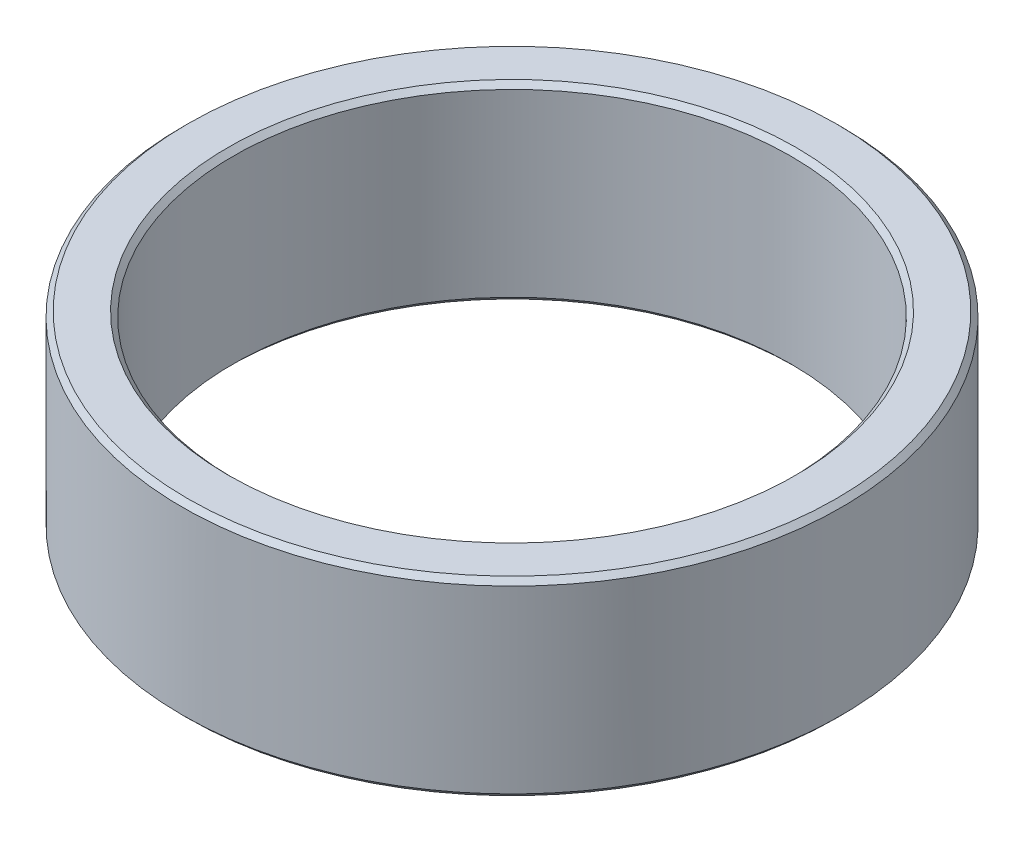
SolidWorks part; units mm, degrees
ref_plane "Front Plane" through (0, 0, 0) normal (0, 0, 1) x (1, 0, 0)
ref_plane "Top Plane" through (0, 0, 0) normal (0, 1, 0) x (1, 0, 0)
ref_plane "Right Plane" through (0, 0, 0) normal (1, 0, 0) x (0, 0, -1)
sketch "Sketch1" plane through (0, 0, 0) normal (0, 1, 0) x (1, 0, 0)
  circle A0 centre (0, 0) radius 11
  circle A1 centre (0, 0) radius 13
  dimension "D1" = 22
  dimension "D2" = 2
extrude "Boss-Extrude1" add sketch "Sketch1" along normal blind 7.5
chamfer "Chamfer1" distance 0.2 angle 45 4 edges at (0, 0, 11) (0, 0, 13) (0, 7.5, 11) (0, 7.5, 13)
